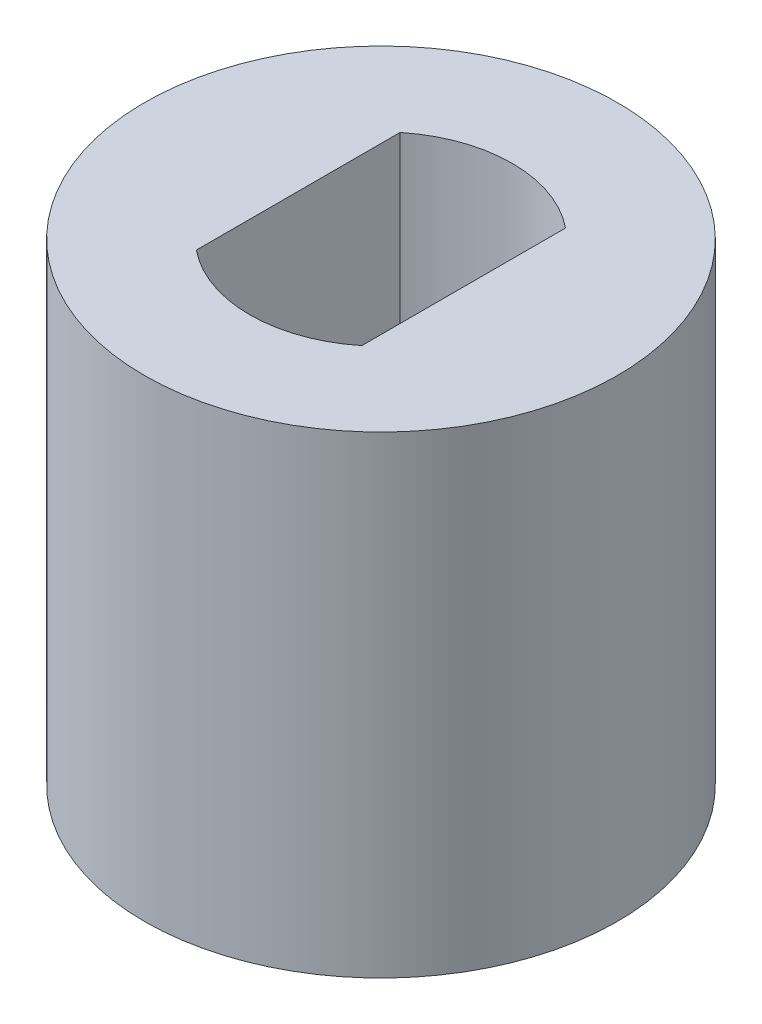
SolidWorks part; units mm, degrees
ref_plane "Front" through (0, 0, 0) normal (0, 0, 1) x (1, 0, 0)
ref_plane "Top" through (0, 0, 0) normal (0, 1, 0) x (1, 0, 0)
ref_plane "Right" through (0, 0, 0) normal (1, 0, 0) x (0, 0, -1)
sketch "Sketch1" plane through (0, 0, 0) normal (0, 1, 0) x (1, 0, 0)
  line L0 (-1.75, 2.1536) -> (-1.75, -2.1536)
  line L1 (1.75, 2.1536) -> (1.75, -2.1536)
  line L2 (-1.75, 0) -> (1.75, 0) construction
  circle A0 centre (0, 0) radius 5
  arc A1 (1.75, 2.1536) -> (-1.75, 2.1536) centre (0, 0) ccw
  arc A2 (-1.75, -2.1536) -> (1.75, -2.1536) centre (0, 0) ccw
  point P10 (0, 0)
  dimension "D1" = 10
  dimension "D2" = 5.55
  dimension "D3" = 3.5
extrude "Boss-Extrude1" add sketch "Sketch1" along normal blind 10
